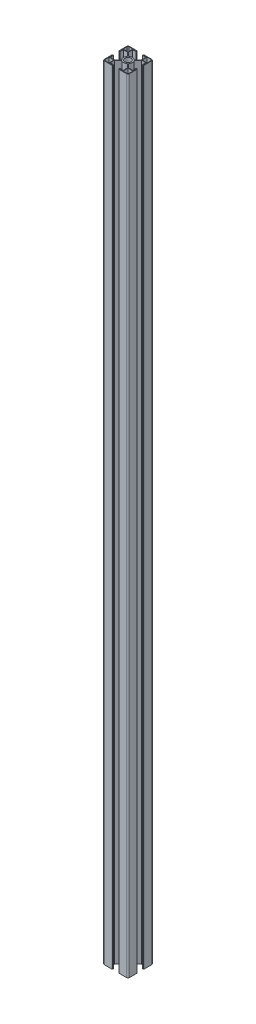
SolidWorks part; units mm, degrees
ref_plane "Plano frontal" through (0, 0, 0) normal (0, 0, 1) x (1, 0, 0)
ref_plane "Plano superior" through (0, 0, 0) normal (0, 1, 0) x (1, 0, 0)
ref_plane "Plano direito" through (0, 0, 0) normal (1, 0, 0) x (0, 0, -1)
sketch "Esboço1" plane through (0, 0, 0) normal (0, 1, 0) x (1, 0, 0)
  line L1 (-18, -20) -> (-5, -20)
  line L2 (-20, -18) -> (-20, -5)
  line L3 (-18, 20) -> (-5, 20)
  line L4 (20, -18) -> (20, -5)
  line L5 (-20, -20) -> (-11.25, -11.25) construction
  line L6 (-20, 20) -> (-11.25, 11.25) construction
  line L7 (11.25, 11.25) -> (20, 20) construction
  line L8 (11.25, -11.25) -> (20, -20) construction
  line L9 (-4.9497, 4.9497) -> (4.9497, -4.9497) construction
  line L10 (0, 20) -> (0, -20) construction
  line L11 (-10.5, -11.2067) -> (-10.5, -18)
  line L12 (-10.5, -18) -> (-5, -18)
  line L13 (-5, -18) -> (-5, -20)
  line L14 (-11.2067, -10.5) -> (-18, -10.5)
  line L15 (-18, -10.5) -> (-18, -5)
  line L16 (-18, -5) -> (-20, -5)
  line L18 (5, -20) -> (18, -20)
  line L19 (20, -5) -> (20, -18)
  line L20 (18, -5) -> (20, -5)
  line L21 (-20, -5) -> (-20, -18)
  line L22 (-5, -20) -> (-18, -20)
  line L23 (18, -10.5) -> (18, -5)
  line L24 (11.2067, -10.5) -> (18, -10.5)
  line L25 (5, -18) -> (5, -20)
  line L26 (10.5, -18) -> (5, -18)
  line L27 (10.5, -11.2067) -> (10.5, -18)
  line L28 (-20, 0) -> (20, 0) construction
  line L31 (10.5, 11.2067) -> (10.5, 18)
  line L32 (10.5, 18) -> (5, 18)
  line L33 (5, 18) -> (5, 20)
  line L34 (11.2067, 10.5) -> (18, 10.5)
  line L35 (18, 10.5) -> (18, 5)
  line L36 (-5, 20) -> (-18, 20)
  line L37 (-20, 5) -> (-20, 18)
  line L38 (18, 5) -> (20, 5)
  line L39 (20, 5) -> (20, 18)
  line L40 (5, 20) -> (18, 20)
  line L41 (-18, 5) -> (-20, 5)
  line L42 (-18, 10.5) -> (-18, 5)
  line L43 (-11.2067, 10.5) -> (-18, 10.5)
  line L44 (-5, 18) -> (-5, 20)
  line L45 (-10.5, 18) -> (-5, 18)
  line L46 (-10.5, 11.2067) -> (-10.5, 18)
  line L48 (-18, 20) -> (-5, 20)
  line L49 (-19.25, 5.75) -> (-18.75, 5.75)
  line L50 (-18.75, 5.75) -> (-18.75, 11.25)
  line L51 (-18.75, 11.25) -> (-11.25, 11.25)
  line L52 (-11.25, 11.25) -> (-11.25, 18.75)
  line L53 (-11.25, 18.75) -> (-5.75, 18.75)
  line L54 (-5.75, 18.75) -> (-5.75, 19.25)
  line L55 (-5.75, 19.25) -> (-17.4697, 19.25)
  line L56 (-19.25, 5.75) -> (-19.25, 17.4697)
  line L58 (19.25, 5.75) -> (19.25, 17.4697)
  line L59 (5.75, 19.25) -> (17.4697, 19.25)
  line L60 (5.75, 18.75) -> (5.75, 19.25)
  line L61 (11.25, 18.75) -> (5.75, 18.75)
  line L62 (11.25, 11.25) -> (11.25, 18.75)
  line L63 (18.75, 11.25) -> (11.25, 11.25)
  line L64 (18.75, 5.75) -> (18.75, 11.25)
  line L65 (19.25, 5.75) -> (18.75, 5.75)
  line L66 (10.5, 11.2067) -> (10.5, 18)
  line L67 (10.5, 18) -> (5, 18)
  line L68 (5, 18) -> (5, 20)
  line L69 (11.2067, 10.5) -> (18, 10.5)
  line L70 (18, 10.5) -> (18, 5)
  line L71 (18, 5) -> (20, 5)
  line L72 (20, 5) -> (20, 18)
  line L73 (5, 20) -> (18, 20)
  line L77 (5, -20) -> (18, -20)
  line L78 (20, -5) -> (20, -18)
  line L79 (18, -5) -> (20, -5)
  line L80 (18, -10.5) -> (18, -5)
  line L81 (11.2067, -10.5) -> (18, -10.5)
  line L82 (5, -18) -> (5, -20)
  line L83 (10.5, -18) -> (5, -18)
  line L84 (10.5, -11.2067) -> (10.5, -18)
  line L85 (19.25, -5.75) -> (18.75, -5.75)
  line L86 (18.75, -5.75) -> (18.75, -11.25)
  line L87 (18.75, -11.25) -> (11.25, -11.25)
  line L88 (11.25, -11.25) -> (11.25, -18.75)
  line L89 (11.25, -18.75) -> (5.75, -18.75)
  line L90 (5.75, -18.75) -> (5.75, -19.25)
  line L91 (5.75, -19.25) -> (17.4697, -19.25)
  line L92 (19.25, -5.75) -> (19.25, -17.4697)
  line L93 (-19.25, -5.75) -> (-19.25, -17.4697)
  line L94 (-5.75, -19.25) -> (-17.4697, -19.25)
  line L95 (-5.75, -18.75) -> (-5.75, -19.25)
  line L96 (-11.25, -18.75) -> (-5.75, -18.75)
  line L97 (-11.25, -11.25) -> (-11.25, -18.75)
  line L98 (-18.75, -11.25) -> (-11.25, -11.25)
  line L99 (-18.75, -5.75) -> (-18.75, -11.25)
  line L100 (-19.25, -5.75) -> (-18.75, -5.75)
  line L101 (-18, -20) -> (-5, -20)
  line L103 (-10.5, -11.2067) -> (-10.5, -18)
  line L104 (-10.5, -18) -> (-5, -18)
  line L105 (-5, -18) -> (-5, -20)
  line L106 (-11.2067, -10.5) -> (-18, -10.5)
  line L107 (-18, -10.5) -> (-18, -5)
  line L108 (-18, -5) -> (-20, -5)
  line L109 (5, -20) -> (18, -20)
  line L110 (20, -5) -> (20, -18)
  line L111 (18, -5) -> (20, -5)
  line L112 (-20, -5) -> (-20, -18)
  line L113 (-5, -20) -> (-18, -20)
  line L114 (18, -10.5) -> (18, -5)
  line L115 (11.2067, -10.5) -> (18, -10.5)
  line L116 (5, -18) -> (5, -20)
  line L117 (10.5, -18) -> (5, -18)
  line L118 (10.5, -11.2067) -> (10.5, -18)
  line L119 (-18, -20) -> (-5, -20)
  line L121 (-4.5838, 5.2904) -> (-10.5, 11.2067)
  line L122 (-5.2904, 4.5838) -> (-11.2067, 10.5)
  line L123 (-5.2904, -4.5838) -> (-11.2067, -10.5)
  line L124 (-4.5838, -5.2904) -> (-10.5, -11.2067)
  line L129 (4.5838, -5.2904) -> (10.5, -11.2067)
  line L130 (5.2904, -4.5838) -> (11.2067, -10.5)
  line L131 (5.2904, 4.5838) -> (11.2067, 10.5)
  line L132 (4.5838, 5.2904) -> (10.5, 11.2067)
  line L133 (5, 20) -> (18, 20)
  line L134 (5, 20) -> (18, 20)
  line L135 (-20, 5) -> (-20, 18)
  line L136 (20, 5) -> (20, 18)
  line L137 (5, -20) -> (18, -20)
  line L138 (5, -20) -> (18, -20)
  line L139 (5, -20) -> (18, -20)
  line L141 (-4.9497, -4.9497) -> (4.9497, 4.9497) construction
  arc A0 (5.2904, -4.5838) -> (5.2904, 4.5838) centre (0, 0) ccw
  arc A1 (-18, -20) -> (-20, -18) centre (-18, -18) cw
  arc A2 (18, -20) -> (20, -18) centre (18, -18) ccw
  arc A3 (18, 20) -> (20, 18) centre (18, 18) cw
  arc A4 (-20, 18) -> (-18, 20) centre (-18, 18) cw
  circle A5 centre (0, 0) radius 5
  arc A6 (18, -20) -> (20, -18) centre (18, -18) ccw
  arc A7 (18, 20) -> (20, 18) centre (18, 18) cw
  arc A8 (18, 20) -> (20, 18) centre (18, 18) cw
  arc A9 (-18, 20) -> (-20, 18) centre (-18, 18) ccw
  arc A10 (-19.25, 17.4697) -> (-17.4697, 19.25) centre (-17.4697, 17.4697) cw
  arc A11 (19.25, 17.4697) -> (17.4697, 19.25) centre (17.4697, 17.4697) ccw
  arc A12 (18, 20) -> (20, 18) centre (18, 18) cw
  arc A13 (20, 18) -> (18, 20) centre (18, 18) ccw
  arc A14 (20, -18) -> (18, -20) centre (18, -18) cw
  arc A15 (18, -20) -> (20, -18) centre (18, -18) ccw
  arc A16 (19.25, -17.4697) -> (17.4697, -19.25) centre (17.4697, -17.4697) cw
  arc A17 (-19.25, -17.4697) -> (-17.4697, -19.25) centre (-17.4697, -17.4697) ccw
  arc A18 (-18, -20) -> (-20, -18) centre (-18, -18) cw
  arc A19 (18, -20) -> (20, -18) centre (18, -18) ccw
  arc A20 (18, -20) -> (20, -18) centre (18, -18) ccw
  arc A21 (-20, -18) -> (-18, -20) centre (-18, -18) ccw
  arc A22 (18, -20) -> (20, -18) centre (18, -18) ccw
  arc A23 (-4.5838, -5.2904) -> (4.5838, -5.2904) centre (0, 0) ccw
  arc A24 (-5.2904, 4.5838) -> (-5.2904, -4.5838) centre (0, 0) ccw
  arc A25 (4.5838, 5.2904) -> (-4.5838, 5.2904) centre (0, 0) ccw
  point P0 (0, 0)
  point P7 (0, 0)
  point P21 (0, 0)
  point P23 (0, 7)
  point P24 (0, 0)
  point P67 (-19, 5)
  point P68 (0, 0)
  point P69 (0, 0)
  point P70 (0, 0)
  point P101 (-4.7698, -5.1234)
  point P114 (-4.6699, -5.2146)
  point P116 (0, 20)
  point P119 (0, 0)
  point P121 (4.6093, -3.9848)
  dimension "D3" = 2
  dimension "D4" = 14
  dimension "D5" = 10
  dimension "D16" = 0.75
  dimension "D17" = 2
  dimension "D1" = 40
  dimension "D2" = 40
  dimension "D6" = 15
  dimension "D7" = 2
  dimension "D8" = 7.5
  dimension "D11" = 0.75
  dimension "D9" = 0.75
  dimension "D10" = 0.75
  dimension "D12" = 0.75
  dimension "D13" = 0.75
  dimension "D14" = 0.75
  dimension "D15" = 0.75
  dimension "D18" = 5.5
  dimension "D19" = 40
  dimension "D20" = 40
  dimension "D21" = 0.5
  dimension "D22" = 0.5
  dimension "D23" = 0.5
  dimension "D24" = 0.5
  dimension "D25" = 0.5
  dimension "D26" = 0.5
extrude "Ressalto-extrusão1" add sketch "Esboço1" along normal blind 1250 contours L132 A25 L121 L46 L45 L44 L3 A4 L37 L41 L42 L43 L122 A24 L123 L14 L15 L16 L2 A1 L1 L13 L12 L11 L124 A23 L129 L27 L26 L25 L18 A2 L4 L20 L23 L24 L130 A0 L131 L34 L35 L38 L39 A3 L40 L33 L32 L31 L92 A16
sketch "Esboço4" plane through (0, 1250, 0) normal (0, 1, 0) x (1, 0, 0)
  line L0 (0, -20) -> (0, 20) construction
  line L1 (-5, 20) -> (-5.75, 20)
  line L2 (-5, 20) -> (-5, 19.5)
  line L3 (-5, 19.5) -> (-5.75, 19.5)
  line L4 (-5.75, 20) -> (-5.75, 19.5)
  line L5 (19.5, 5) -> (19.5, 5.75)
  line L6 (-20, 5) -> (-19.5, 5)
  line L7 (-20, 5) -> (-20, 5.75)
  line L8 (-20, 5.75) -> (-19.5, 5.75)
  line L9 (-19.5, 5) -> (-19.5, 5.75)
  line L10 (20, 5.75) -> (19.5, 5.75)
  line L11 (20, 5) -> (20, 5.75)
  line L12 (20, 5) -> (19.5, 5)
  line L13 (5.75, 20) -> (5.75, 19.5)
  line L14 (5, 19.5) -> (5.75, 19.5)
  line L15 (5, 20) -> (5, 19.5)
  line L16 (5, 20) -> (5.75, 20)
  line L17 (20, 0) -> (-20, 0) construction
  line L18 (5, -20) -> (5.75, -20)
  line L19 (5, -20) -> (5, -19.5)
  line L20 (5, -19.5) -> (5.75, -19.5)
  line L21 (5.75, -20) -> (5.75, -19.5)
  line L22 (20, -5) -> (19.5, -5)
  line L23 (20, -5) -> (20, -5.75)
  line L24 (20, -5.75) -> (19.5, -5.75)
  line L25 (-19.5, -5) -> (-19.5, -5.75)
  line L26 (-20, -5.75) -> (-19.5, -5.75)
  line L27 (-20, -5) -> (-20, -5.75)
  line L28 (-20, -5) -> (-19.5, -5)
  line L29 (19.5, -5) -> (19.5, -5.75)
  line L30 (-5.75, -20) -> (-5.75, -19.5)
  line L31 (-5, -19.5) -> (-5.75, -19.5)
  line L32 (-5, -20) -> (-5, -19.5)
  line L33 (-5, -20) -> (-5.75, -20)
  point P10 (0, 0)
  point P26 (0, 0)
  dimension "D1" = 0.75
  dimension "D2" = 0.5
  dimension "D3" = 0.5
  dimension "D4" = 0.75
extrude "Corte-extrusão1" cut sketch "Esboço4" against normal up to surface (1250 mm away) up to face at (14.2043, 0, 14.2043)
